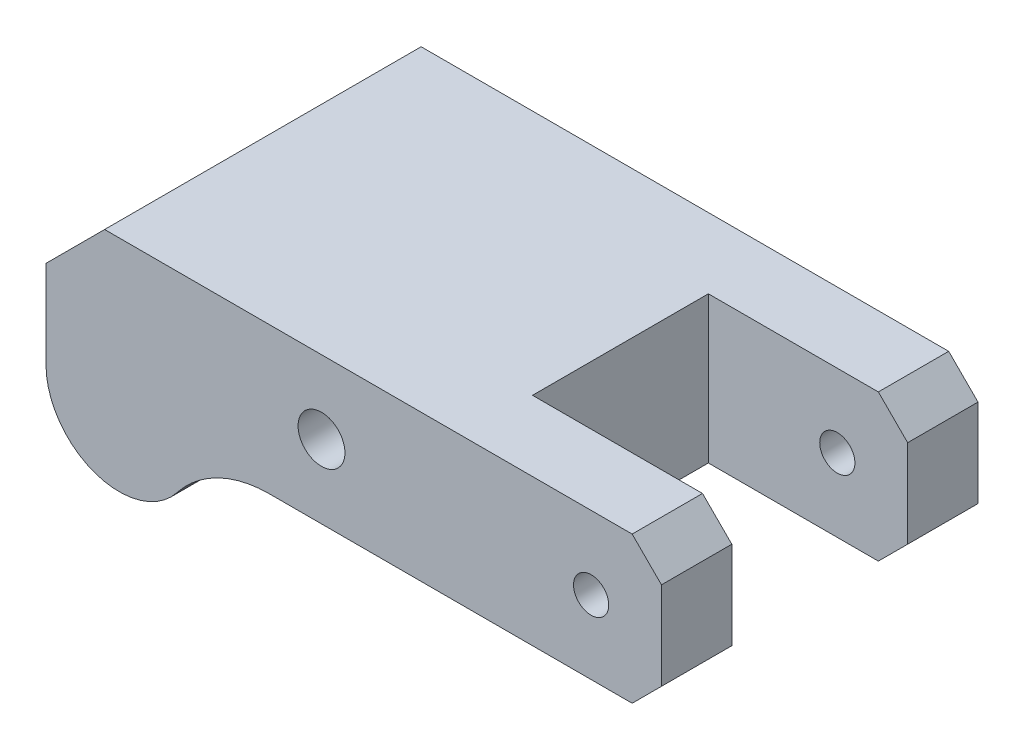
SolidWorks part; units mm, degrees
ref_plane "Piano frontale" through (0, 0, 0) normal (0, 0, 1) x (1, 0, 0)
ref_plane "Piano superiore" through (0, 0, 0) normal (0, 1, 0) x (1, 0, 0)
ref_plane "Piano destro" through (0, 0, 0) normal (1, 0, 0) x (0, 0, -1)
sketch "Schizzo1" plane through (0, 0, 0) normal (0, 0, 1) x (1, 0, 0)
  line L0 (-71.5587, 25) -> (33.4413, 25)
  line L1 (33.4413, 25) -> (33.4413, 0)
  line L2 (33.4413, 0) -> (-33.4413, 0)
  line L3 (-71.5587, 25) -> (-71.5587, 0)
  arc A0 (-71.5587, 0) -> (-49.2059, -7.6923) centre (-59.0587, 0) ccw
  arc A1 (-33.4413, 0) -> (-49.2059, -7.6923) centre (-33.4413, -20) ccw
  dimension "D3" = 25
  dimension "D4" = 40
  dimension "D1" = 105
  dimension "D2" = 25
extrude "Estrusione-Estrusione1" add sketch "Schizzo1" along normal mid plane 54
chamfer "Smusso1" distance 10 angle 45 1 edges at (-71.5587, 25, 0)
chamfer "Smusso2" distance 5 angle 45 2 edges at (33.4413, 0, 0) (33.4413, 25, 0)
sketch "Schizzo2" plane through (0, 25, 0) normal (0, 1, 0) x (1, 0, 0)
  line L0 (33.4413, 15) -> (-0.5587, 15)
  line L1 (33.4413, 27) -> (33.4413, -27) construction
  line L2 (-0.5587, 15) -> (-0.5587, -15)
  line L3 (-0.5587, -15) -> (33.4413, -15)
  line L4 (33.4413, -15) -> (33.4413, 15)
  point P4 (-0.5587, 0)
  dimension "D1" = 30
  dimension "D2" = 34
extrude "Taglio-Estrusione1" cut sketch "Schizzo2" against normal through all
sketch "Schizzo3" plane through (0, 0, 27) normal (0, 0, 1) x (1, 0, 0)
  line L0 (33.4413, 5) -> (33.4413, 20) construction
  circle A0 centre (21.4413, 12.5) radius 3
  circle A1 centre (-24.5587, 12.5) radius 4
  point P6 (33.4413, 12.5)
  dimension "D2" = 8
  dimension "D4" = 6
  dimension "D1" = 58
  dimension "D3" = 12
extrude "Taglio-Estrusione2" cut sketch "Schizzo3" against normal through all
